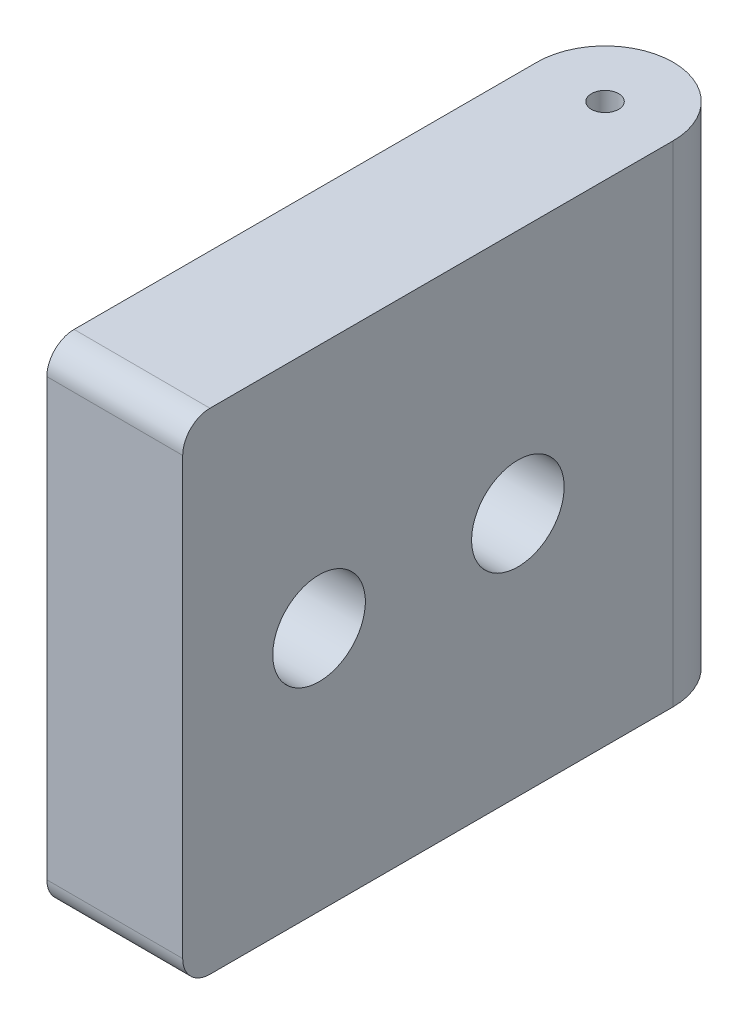
SolidWorks part; units mm, degrees
ref_plane "Front Plane" through (0, 0, 0) normal (0, 0, 1) x (1, 0, 0)
ref_plane "Top Plane" through (0, 0, 0) normal (0, 1, 0) x (1, 0, 0)
ref_plane "Right Plane" through (0, 0, 0) normal (1, 0, 0) x (0, 0, -1)
sketch "Sketch1" plane through (0, 0, 0) normal (0, 1, 0) x (1, 0, 0)
  line L0 (-2.5, -17.9941) -> (-2.5, 0)
  line L1 (2.5, -18.006) -> (2.5, 0)
  line L3 (-2.5, -17.9941) -> (2.5, -18.006)
  arc A0 (2.5, 0) -> (-2.5, 0) centre (0, 0) ccw
  circle A1 centre (0, 0) radius 0.5
  dimension "D2" = 2.5
  dimension "D4" = 5
  dimension "D3" = 18
extrude "Boss-Extrude1" add sketch "Sketch1" along normal blind 18
sketch "Sketch3" plane through (0, 0, 0) normal (1, 0, 0) x (0, 0, -1)
  line L0 (2.5, 13) -> (-2.5, 13)
  line L1 (2.5, 0) -> (2.5, 18) construction
  line L2 (-2.5, 13) -> (-2.5, 5)
  line L3 (-2.5, 5) -> (2.5, 5)
  line L4 (2.5, 5) -> (2.5, 13)
  line L5 (2.5, 18) -> (0, 18) construction
  dimension "D1" = 8
  dimension "D2" = 5
  dimension "D3" = 5
extrude "Cut-Extrude2" [suppressed] cut sketch "Sketch3" against normal through all both and the other way through all
sketch "Sketch4" plane through (-2.5, 0, 0) normal (1, 0, 0) x (0, 0, -1)
  line L1 (-18.006, 18) -> (0, 18) construction
  line L2 (2.5, 0) -> (2.5, 18) construction
  circle A0 centre (-5.7, 9) radius 1.5 construction
  circle A1 centre (-13, 9) radius 1.5 construction
  dimension "D4" = 3
  dimension "D5" = 3
  dimension "D1" = 8.2
  dimension "D2" = 7.3
  dimension "D3" = 9
fillet "Fillet2" radius 1 2 edges at (0, 0, 18.0001) (0, 18, 18.0001)
fillet "Fillet3" [suppressed] radius 4
hole_wizard "CSK for M3 Flat Head Machine Screw2" positions "Sketch18" profile "Sketch17" countersink size "M3" standard "ANSI Metric" end condition through all
sketch "Sketch18" plane through (-2.5, 0, 0) normal (-1, 0, 0) x (0, 0, 1)
  point P0 (5.7, 9)
  point P3 (13, 9)
sketch "Sketch17" plane through (-2.5, 9, 5.7) normal (0, 1, 0) x (0, 0, 1)
  line L0 (0, 0) -> (0, 5)
  line L1 (0, 5) -> (1.7, 5)
  line L2 (1.7, 5) -> (1.7, 1.45)
  line L3 (1.7, 1.45) -> (3.15, 0)
  line L5 (3.15, 0) -> (0, 0)
  line L6 (-1.7, 1.45) -> (-3.15, 0) construction
  line L11 (0, -6.35) -> (0, 107.95) construction
  dimension "Thru Hole Dia." = 3.4
  dimension "Thru Hole Depth" = 5
  dimension "Near C'Sink Dia." = 6.3
  dimension "Near C'Sink Angle" = 90
equation "\"D3\"=5"
